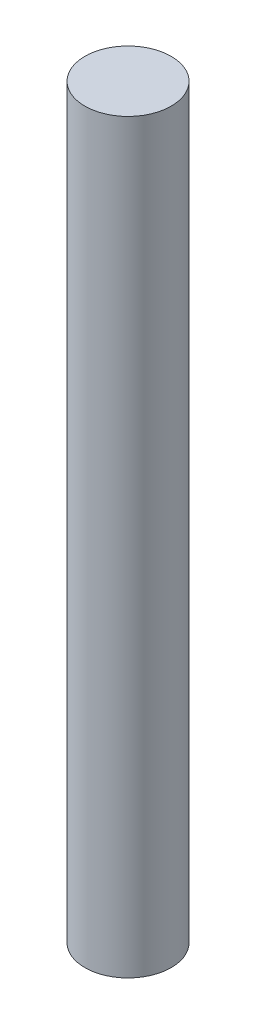
SolidWorks part; units mm, degrees
ref_plane "Front Plane" through (0, 0, 0) normal (0, 0, 1) x (1, 0, 0)
ref_plane "Top Plane" through (0, 0, 0) normal (0, 1, 0) x (1, 0, 0)
ref_plane "Right Plane" through (0, 0, 0) normal (1, 0, 0) x (0, 0, -1)
sketch "Sketch1" plane through (0, 0, 0) normal (0, 1, 0) x (1, 0, 0)
  circle A0 centre (0, 0) radius 0.725
  dimension "D1" = 1.45
extrude "Boss-Extrude1" add sketch "Sketch1" along normal blind 12.53
